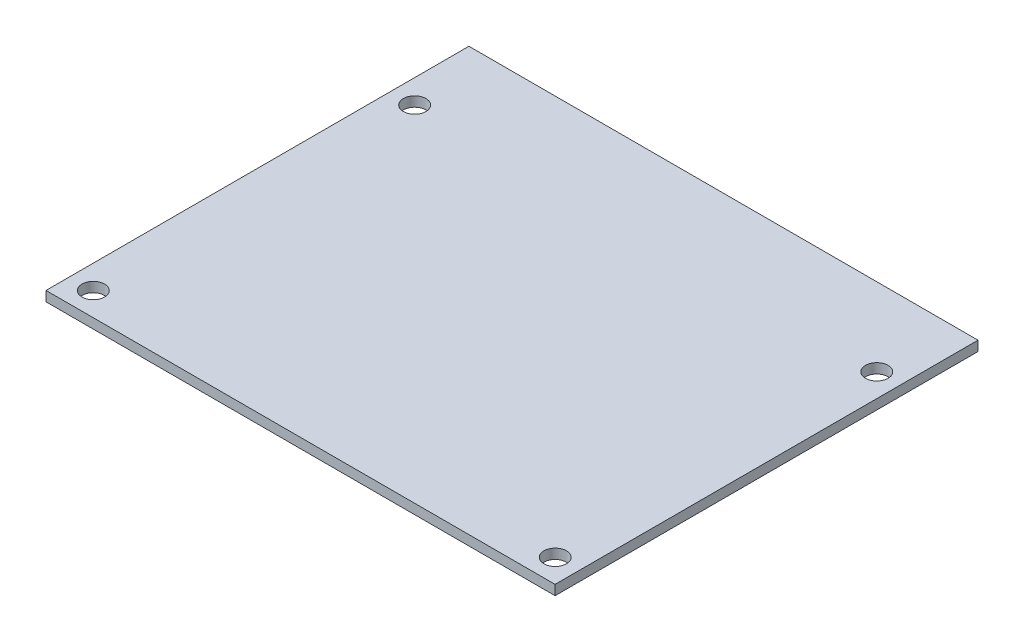
SolidWorks part; units mm, degrees
ref_plane "Front" through (0, 0, 0) normal (0, 0, 1) x (1, 0, 0)
ref_plane "Top" through (0, 0, 0) normal (0, 1, 0) x (1, 0, 0)
ref_plane "Right" through (0, 0, 0) normal (1, 0, 0) x (0, 0, -1)
sketch "Sketch1" plane through (0, 0, 0) normal (0, 1, 0) x (1, 0, 0)
  line L1 (-41.275, 34.29) -> (41.275, 34.29)
  line L2 (-41.275, 34.29) -> (-41.275, -34.29)
  line L3 (-41.275, -34.29) -> (41.275, -34.29)
  line L4 (41.275, 34.29) -> (41.275, -34.29)
  line L5 (-41.275, 34.29) -> (41.275, -34.29) construction
  line L6 (-41.275, -34.29) -> (41.275, 34.29) construction
  point P0 (0, 0)
  dimension "D1" = 68.58
  dimension "D2" = 82.55
extrude "Boss-Extrude1" add sketch "Sketch1" along normal blind 1.6002
sketch "Sketch2" plane through (0, 1.6002, 0) normal (0, 1, 0) x (1, 0, 0)
  circle A0 centre (37.4882, -30.4837) radius 1.8288
  dimension "D1" = 3.6576
extrude "Cut-Extrude1" cut sketch "Sketch2" against normal through all
sketch "Sketch3" plane through (0, 1.6002, 0) normal (0, 1, 0) x (1, 0, 0)
  circle A0 centre (37.5134, 21.6352) radius 1.8288
  circle A1 centre (-37.4224, 21.6352) radius 1.8288
  circle A2 centre (-37.4224, -30.4699) radius 1.8288
  dimension "D1" = 3.6576
extrude "Cut-Extrude2" cut sketch "Sketch3" against normal through all
